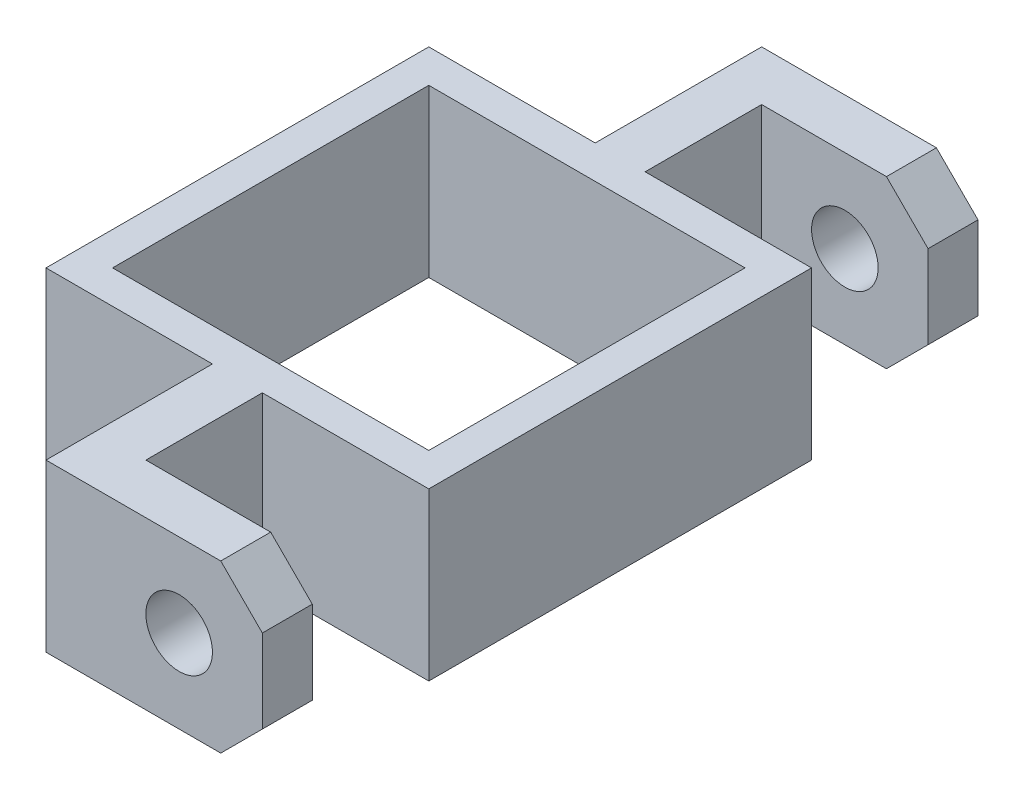
SolidWorks part; units mm, degrees
ref_plane "Alzado" through (0, 0, 0) normal (0, 0, 1) x (1, 0, 0)
ref_plane "Planta" through (0, 0, 0) normal (0, 1, 0) x (1, 0, 0)
ref_plane "Vista lateral" through (0, 0, 0) normal (1, 0, 0) x (0, 0, -1)
sketch "Croquis1" plane through (0, 0, 0) normal (0, 1, 0) x (1, 0, 0)
  line L1 (-9.5, 9.5) -> (9.5, 9.5)
  line L2 (-9.5, 9.5) -> (-9.5, -9.5)
  line L3 (-9.5, -9.5) -> (9.5, -9.5)
  line L4 (9.5, 9.5) -> (9.5, -9.5)
  line L5 (-9.5, 9.5) -> (9.5, -9.5) construction
  line L6 (-9.5, -9.5) -> (9.5, 9.5) construction
  line L7 (-11.5, 11.5) -> (11.5, 11.5)
  line L8 (-11.5, 11.5) -> (-11.5, -11.5)
  line L9 (-11.5, -11.5) -> (11.5, -11.5)
  line L10 (11.5, 11.5) -> (11.5, -11.5)
  line L11 (-11.5, 11.5) -> (11.5, -11.5) construction
  line L12 (-11.5, -11.5) -> (11.5, 11.5) construction
  point P0 (0, 0)
  point P6 (0, 0)
  dimension "D1" = 2
  dimension "D2" = 23
extrude "Saliente-Extruir1" add sketch "Croquis1" along normal blind 10
sketch "Croquis2" plane through (0, 0, 0) normal (1, 0, 0) x (0, 0, -1)
  line L1 (11.5, 10) -> (18.5, 10)
  line L2 (11.5, 10) -> (11.5, 0)
  line L3 (11.5, 0) -> (18.5, 0)
  line L4 (18.5, 10) -> (18.5, 0)
  dimension "D1" = 7
extrude "Saliente-Extruir2" add sketch "Croquis2" along normal blind 1.5 and the other way blind 1.5
sketch "Croquis3" plane through (0, 0, -18.5) normal (0, 0, -1) x (-1, 0, 0)
  line L0 (-9, 10) -> (-11.5, 7.5)
  line L1 (-11.5, 7.5) -> (-11.5, 2.5)
  line L2 (-11.5, 2.5) -> (-9, 0)
  line L4 (-9, 10) -> (-9, 0) construction
  line L5 (-9, 10) -> (1.5, 10)
  line L6 (1.5, 10) -> (1.5, 0)
  line L7 (1.5, 0) -> (-9, 0)
  line L9 (0, 0) -> (0, 10) construction
  dimension "D1" = 11.5
  dimension "D2" = 5
  dimension "D3" = 45
extrude "Saliente-Extruir3" add sketch "Croquis3" along normal blind 3
sketch "Croquis4" plane through (0, 0, -21.5) normal (0, 0, -1) x (-1, 0, 0)
  line L0 (-11.5, 5) -> (1.5, 5) construction
  line L1 (-11.5, 7.5) -> (-11.5, 2.5) construction
  line L2 (1.5, 0) -> (1.5, 10) construction
  line L3 (-9, 10) -> (-9, 0) construction
  circle A0 centre (-6.5, 5) radius 2
  dimension "D1" = 4
  dimension "D2" = 5
extrude "Cortar-Extruir1" cut sketch "Croquis4" against normal blind 4
mirror "Simetría1" about plane through (0, 0, 0) normal (0, 0, 1) of "Cortar-Extruir1", "Saliente-Extruir3", "Saliente-Extruir2"
